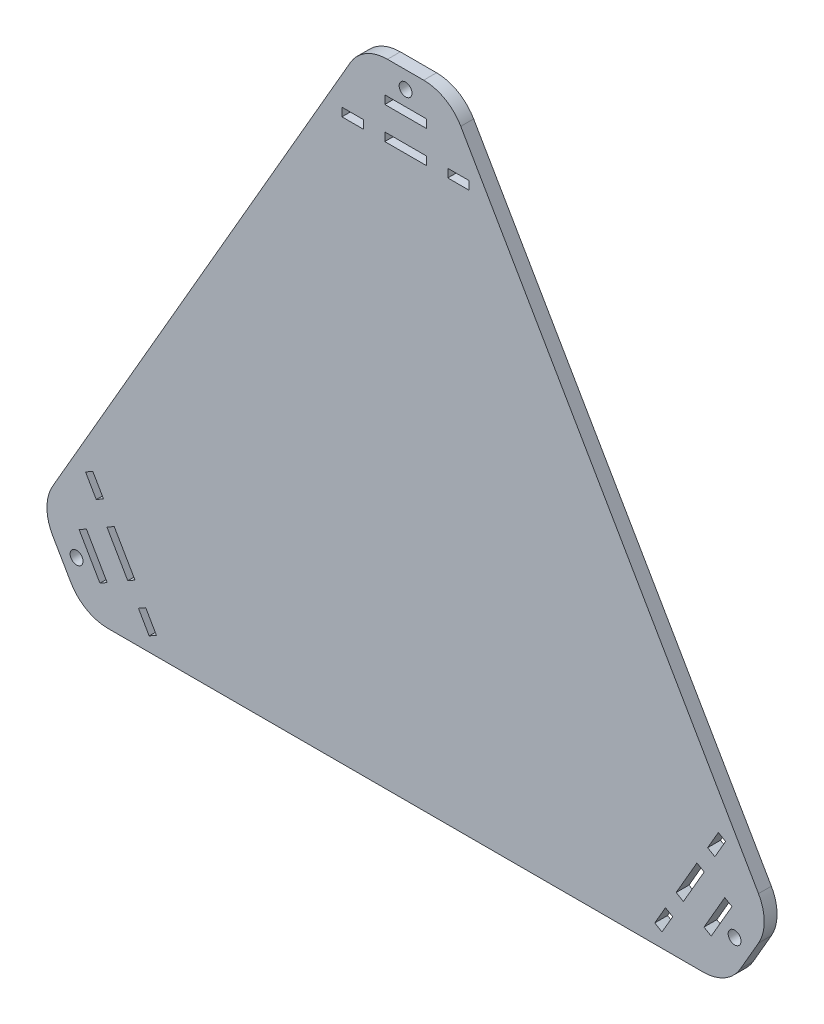
SolidWorks part; units mm, degrees
ref_plane "Спереди" through (0, 0, 0) normal (0, 0, 1) x (1, 0, 0)
ref_plane "Сверху" through (0, 0, 0) normal (0, 1, 0) x (1, 0, 0)
ref_plane "Справа" through (0, 0, 0) normal (1, 0, 0) x (0, 0, -1)
other "Configuration Table"
sketch "Эскиз1" plane through (0, 0, 0) normal (0, 0, 1) x (1, 0, 0)
  line L0 (0, 0) -> (-145.8465, -84.2045) construction
  line L1 (-69.4893, -55) -> (69.4893, -55)
  line L2 (82.376, -32.6795) -> (12.8868, 87.6795)
  line L3 (-12.8868, 87.6795) -> (-82.376, -32.6795)
  line L4 (-71.3426, -46.79) -> (-76.1926, -38.3895)
  line L6 (-82.376, -42.6795) -> (-78.1495, -50)
  line L7 (82.376, -42.6795) -> (78.1495, -50)
  line L8 (4.2265, 92.6795) -> (-4.2265, 92.6795)
  line L12 (0, 0) -> (80.2628, -46.3397) construction
  line L13 (-71.3426, -46.79) -> (-69.6539, -45.815)
  line L14 (-76.1926, -38.3895) -> (-74.5039, -37.4145)
  line L15 (-69.6539, -45.815) -> (-74.5039, -37.4145)
  line L16 (-71.3426, -46.79) -> (-74.5039, -37.4145) construction
  line L17 (-76.1926, -38.3895) -> (-69.6539, -45.815) construction
  line L18 (-4.85, 85.1795) -> (-4.85, 83.2295)
  line L19 (4.85, 83.2295) -> (-4.85, 83.2295)
  line L20 (4.85, 85.1795) -> (4.85, 83.2295)
  line L21 (4.85, 85.1795) -> (-4.85, 85.1795)
  line L22 (76.1926, -38.3895) -> (71.3426, -46.79)
  line L23 (76.1926, -38.3895) -> (74.5039, -37.4145)
  line L24 (74.5039, -37.4145) -> (69.6539, -45.815)
  line L25 (71.3426, -46.79) -> (69.6539, -45.815)
  line L26 (-64.8474, -43.04) -> (-69.6974, -34.6395)
  line L27 (-64.8474, -43.04) -> (-63.1587, -42.065)
  line L28 (-69.6974, -34.6395) -> (-68.0087, -33.6645)
  line L29 (-63.1587, -42.065) -> (-68.0087, -33.6645)
  line L30 (4.85, 77.6795) -> (4.85, 75.7295)
  line L31 (4.85, 75.7295) -> (-4.85, 75.7295)
  line L32 (-4.85, 77.6795) -> (-4.85, 75.7295)
  line L33 (4.85, 77.6795) -> (-4.85, 77.6795)
  line L34 (69.6974, -34.6395) -> (64.8474, -43.04)
  line L35 (64.8474, -43.04) -> (63.1587, -42.065)
  line L36 (68.0087, -33.6645) -> (63.1587, -42.065)
  line L37 (69.6974, -34.6395) -> (68.0087, -33.6645)
  line L38 (70.5087, -29.3344) -> (72.1974, -30.3094)
  line L39 (70.5087, -29.3344) -> (73.0087, -25.0043)
  line L40 (72.1974, -30.3094) -> (74.6974, -25.9793)
  line L41 (73.0087, -25.0043) -> (74.6974, -25.9793)
  line L42 (62.3474, -47.3701) -> (59.8474, -51.7002)
  line L43 (58.1587, -50.7252) -> (59.8474, -51.7002)
  line L44 (60.6587, -46.3951) -> (58.1587, -50.7252)
  line L45 (60.6587, -46.3951) -> (62.3474, -47.3701)
  line L46 (-9.85, 75.7295) -> (-9.85, 77.6795)
  line L47 (-9.85, 75.7295) -> (-14.85, 75.7295)
  line L48 (-14.85, 75.7295) -> (-14.85, 77.6795)
  line L49 (-9.85, 77.6795) -> (-14.85, 77.6795)
  line L50 (9.85, 77.6795) -> (14.85, 77.6795)
  line L51 (14.85, 75.7295) -> (14.85, 77.6795)
  line L52 (9.85, 75.7295) -> (14.85, 75.7295)
  line L53 (9.85, 75.7295) -> (9.85, 77.6795)
  line L54 (-60.6587, -46.3951) -> (-62.3474, -47.3701)
  line L55 (-60.6587, -46.3951) -> (-58.1587, -50.7252)
  line L56 (-58.1587, -50.7252) -> (-59.8474, -51.7002)
  line L57 (-62.3474, -47.3701) -> (-59.8474, -51.7002)
  line L58 (-70.5087, -29.3344) -> (-73.0087, -25.0043)
  line L59 (-73.0087, -25.0043) -> (-74.6974, -25.9793)
  line L60 (-72.1974, -30.3094) -> (-74.6974, -25.9793)
  line L61 (-70.5087, -29.3344) -> (-72.1974, -30.3094)
  circle A0 centre (0, 0) radius 55 construction
  circle A1 centre (-76.7987, -44.3397) radius 1.5
  circle A2 centre (0, 88.6795) radius 1.5
  circle A3 centre (76.7987, -44.3397) radius 1.5
  arc A5 (-69.4893, -55) -> (-78.1495, -50) centre (-69.4893, -45) cw
  arc A6 (-82.376, -42.6795) -> (-82.376, -32.6795) centre (-73.7158, -37.6795) cw
  arc A7 (-4.2265, 92.6795) -> (-12.8868, 87.6795) centre (-4.2265, 82.6795) ccw
  arc A8 (4.2265, 92.6795) -> (12.8868, 87.6795) centre (4.2265, 82.6795) cw
  arc A9 (82.376, -32.6795) -> (82.376, -42.6795) centre (73.7158, -37.6795) cw
  arc A10 (78.1495, -50) -> (69.4893, -55) centre (69.4893, -45) cw
  point P4 (-72.9232, -42.1022)
  point P9 (-80.2628, -46.3397)
  point P16 (-75.2628, -55)
  point P46 (71.353, -29.8219)
  point P49 (-85.2628, -37.6795)
  point P52 (-10, 92.6795)
  point P55 (10, 92.6795)
  point P58 (85.2628, -37.6795)
  point P61 (75.2628, -55)
  dimension "D5" = 3
  dimension "D12" = 5
  dimension "D13" = 10
  dimension "D14" = 10
  dimension "D2" = 110
  dimension "D1" = 20
  dimension "D3" = 1.95
  dimension "D4" = 20
  dimension "D6" = 9.7
  dimension "D7" = 4
  dimension "D8" = 20
  dimension "D9" = 3.5
  dimension "D10" = 5.55
  dimension "D11" = 1.95
  dimension "D15" = 5
extrude "Бобышка-Вытянуть1" add sketch "Эскиз1" along normal blind 3
